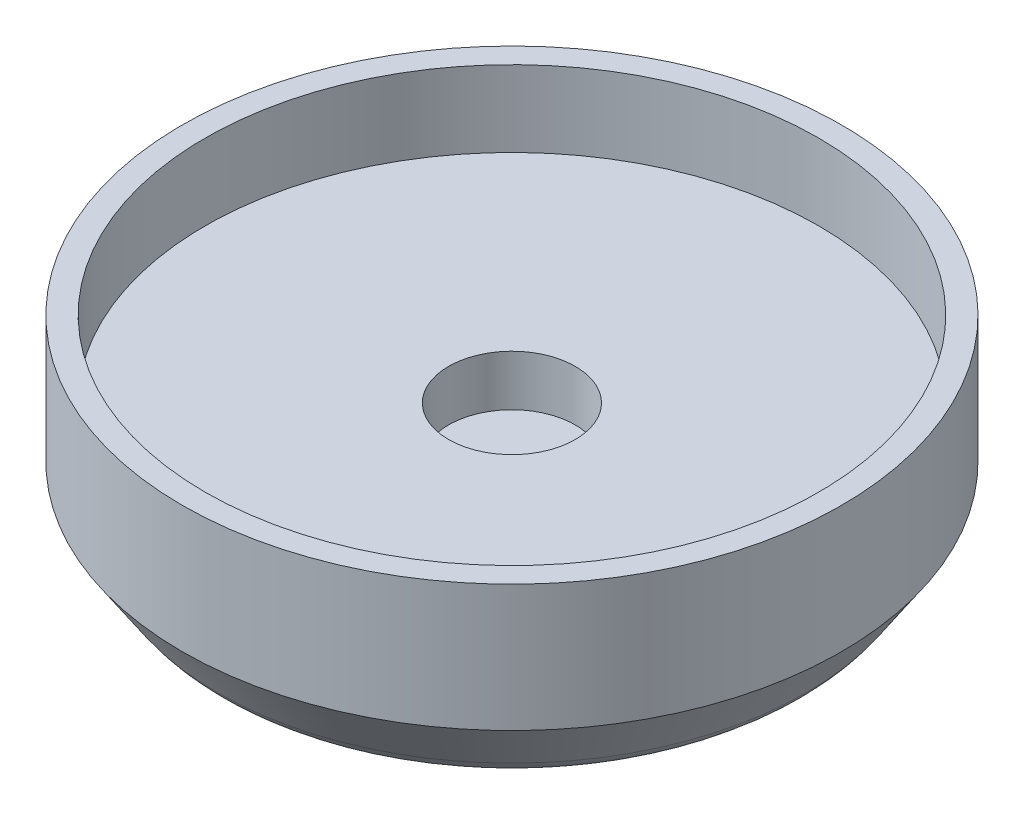
SolidWorks part; units mm, degrees
other "标注1"
sketch "草图5" plane through (-13, 5, -13) normal (-0.9407, 0.0558, -0.3347) x (-0.3069, 0.2808, 0.9094)
ref_plane "Front Plane" through (0, 0, 0) normal (0, 0, 1) x (1, 0, 0)
ref_plane "Top Plane" through (0, 0, 0) normal (0, 1, 0) x (1, 0, 0)
ref_plane "Right Plane" through (0, 0, 0) normal (1, 0, 0) x (0, 0, -1)
other "Configuration Table"
sketch "草图1" plane through (0, 0, 0) normal (0, 1, 0) x (1, 0, 0)
  circle A0 centre (0, 0) radius 13
  dimension "D1" = 26
extrude "凸台-拉伸1" add sketch "草图1" along normal blind 5
sketch "草图2" plane through (0, 5, 0) normal (0, 1, 0) x (1, 0, 0)
  circle A0 centre (0, 0) radius 12
  dimension "D1" = 24
extrude "切除-拉伸1" cut sketch "草图2" against normal blind 3
sketch "草图3" plane through (0, 2, 0) normal (0, 1, 0) x (1, 0, 0)
  circle A0 centre (0, 0) radius 2.5
  dimension "D1" = 5
extrude "切除-拉伸2" cut sketch "草图3" against normal blind 2
ref_plane "基准面1" through (0, -3, 0) normal (0, -1, 0) x (-1, 0, 0)
sketch "草图4" plane through (0, -3, 0) normal (0, -1, 0) x (-1, 0, 0)
  circle A0 centre (0, 0) radius 13 construction
  circle A2 centre (0, 0) radius 11
  dimension "D1" = 2
loft "放样1" add profiles "草图4" section "草图4" section edge at (0, 0, 13)
fillet "圆角1" radius 2 1 edges at (0, -3, -11)
sketch "草图7" plane through (0, 2, 0) normal (0, 1, 0) x (1, 0, 0)
  circle A0 centre (0, 0) radius 12.1
  dimension "D1" = 24.2
extrude "切除-拉伸3" cut sketch "草图7" along normal through all
